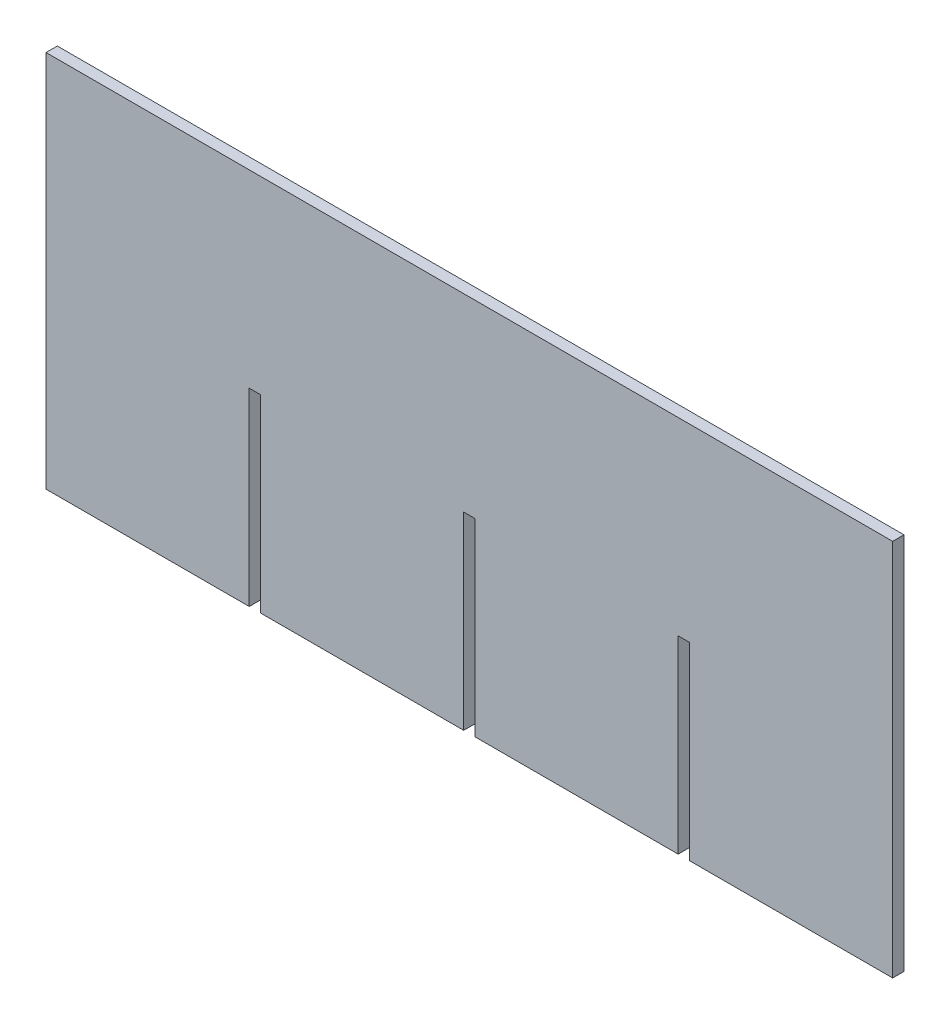
SolidWorks part; units mm, degrees
ref_plane "Front Plane" through (0, 0, 0) normal (0, 0, 1) x (1, 0, 0)
ref_plane "Top Plane" through (0, 0, 0) normal (0, 1, 0) x (1, 0, 0)
ref_plane "Right Plane" through (0, 0, 0) normal (1, 0, 0) x (0, 0, -1)
sketch "Sketch1" plane through (0, 0, 0) normal (0, 0, 1) x (1, 0, 0)
  line L1 (75, -33.5) -> (-75, -33.5)
  line L2 (75, -33.5) -> (75, 33.5)
  line L3 (75, 33.5) -> (-75, 33.5)
  line L4 (-75, -33.5) -> (-75, 33.5)
  line L5 (75, -33.5) -> (-75, 33.5) construction
  line L6 (75, 33.5) -> (-75, -33.5) construction
  point P0 (0, 0)
  dimension "D1" = 150
  dimension "D2" = 67
extrude "Boss-Extrude1" add sketch "Sketch1" along normal blind 2
sketch "Sketch2" plane through (0, 0, 2) normal (0, 0, 1) x (1, 0, 0)
  line L0 (-75, -33.5) -> (-39, -33.5)
  line L1 (-75, -33.5) -> (75, -33.5) construction
  line L2 (-37, -33.5) -> (-37, 0)
  line L3 (-37, 0) -> (-39, 0)
  line L4 (-39, 0) -> (-39, -33.5)
  line L5 (-37, -33.5) -> (-39, -33.5)
  line L6 (-19, 17.1563) -> (-19, -31.4144) construction
  line L7 (-1, -33.5) -> (1, -33.5)
  line L8 (-1, 0) -> (1, 0)
  line L9 (1, 0) -> (1, -33.5)
  line L10 (-1, -33.5) -> (-1, 0)
  line L11 (19, 17.1563) -> (19, -31.4144) construction
  line L12 (39, -33.5) -> (37, -33.5)
  line L13 (39, 0) -> (37, 0)
  line L14 (37, 0) -> (37, -33.5)
  line L15 (39, -33.5) -> (39, 0)
  dimension "D1" = 36
  dimension "D2" = 2
  dimension "D3" = 33.5
  dimension "D4" = 18
  dimension "D5" = 18
extrude "Cut-Extrude1" cut sketch "Sketch2" against normal through all contours L5 L2 L3 L4 | L10 L8 L9 L7 | L14 L12 L15 L13
